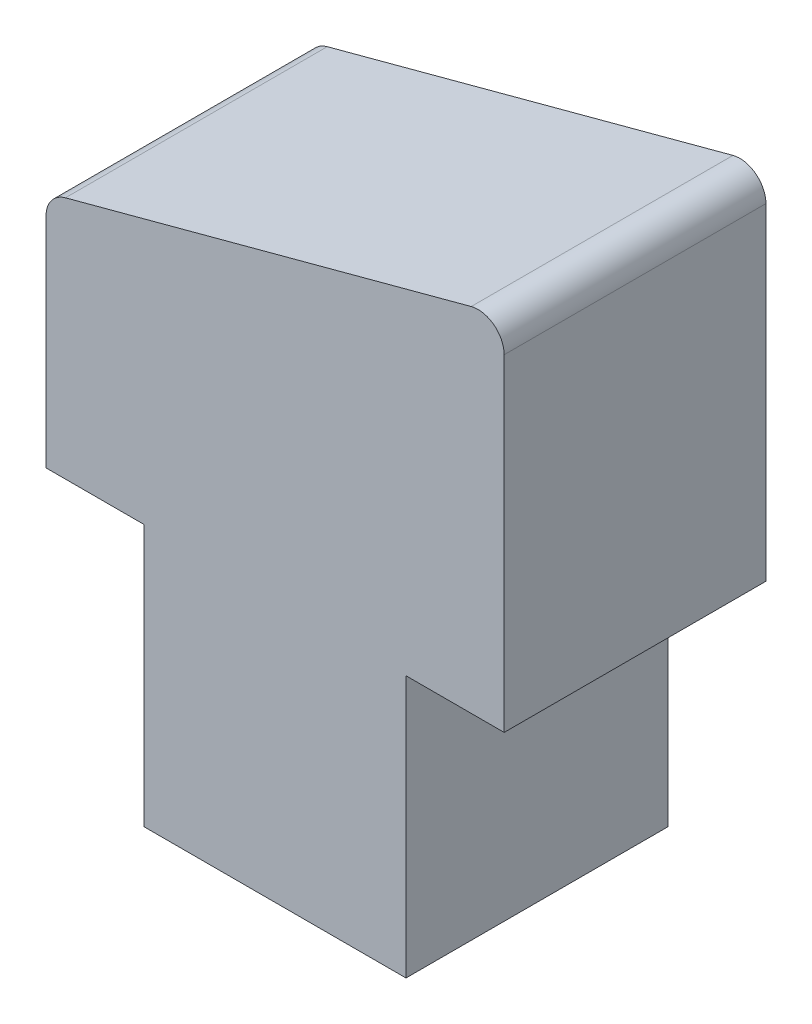
SolidWorks part; units mm, degrees
ref_plane "정면" through (0, 0, 0) normal (0, 0, 1) x (1, 0, 0)
ref_plane "윗면" through (0, 0, 0) normal (0, 1, 0) x (1, 0, 0)
ref_plane "우측면" through (0, 0, 0) normal (1, 0, 0) x (0, 0, -1)
sketch "Sketch2" plane through (0, 0, 0) normal (0, 1, 0) x (1, 0, 0)
  line L1 (-75, 30) -> (75, 30)
  line L2 (-75, 30) -> (-75, -30)
  line L3 (-75, -30) -> (75, -30)
  line L4 (75, 30) -> (75, -30)
  point P4 (0, 30)
  point P6 (-75, 0)
  dimension "D1" = 150
  dimension "D2" = 60
extrude "Extrude1" add sketch "Sketch2" along normal blind 20
sketch "Sketch3" plane through (0, 20, 0) normal (0, 1, 0) x (1, 0, 0)
  line L1 (-10.2, 23.1) -> (10.2, 23.1)
  line L2 (-10.2, 23.1) -> (-10.2, 2.7)
  line L3 (-10.2, 2.7) -> (10.2, 2.7)
  line L4 (10.2, 23.1) -> (10.2, 2.7)
  line L5 (-10.2, -2.7) -> (10.2, -2.7)
  line L6 (-10.2, -2.7) -> (-10.2, -23.1)
  line L7 (-10.2, -23.1) -> (10.2, -23.1)
  line L8 (10.2, -2.7) -> (10.2, -23.1)
  point P8 (0, -2.7)
  point P10 (0, 2.7)
  dimension "D1" = 20.4
  dimension "D2" = 20.4
  dimension "D3" = 20.4
  dimension "D4" = 20.4
  dimension "D5" = 5.4
  dimension "D6" = 2.7
extrude "Extrude2" cut sketch "Sketch3" against normal blind 20
sketch "Sketch4" plane through (0, 0, 0) normal (0, 0, 1) x (1, 0, 0)
  line L0 (0, 0) -> (0, 35) construction
  line L1 (0, 27.5) -> (-75, 47.5962) construction
  line L2 (-75, 20) -> (75, 20) construction
  line L3 (-75, 20) -> (-75, 0) construction
  line L4 (-75, 20) -> (-75, 47.5962)
  line L5 (-75, 47.5962) -> (-40, 38.218)
  line L6 (-40, 38.218) -> (-40, 20)
  line L7 (-75, 20) -> (-40, 20)
  dimension "D1" = 35
  dimension "D2" = 7.5
  dimension "D3" = 15
  dimension "D4" = 35
extrude "Extrude3" add sketch "Sketch4" along normal mid plane 20
mirror "Mirror1" about plane through (0, 0, 0) normal (1, 0, 0) of "Extrude3"
sketch "Sketch5" plane through (0, 0, -10) normal (0, 0, -1) x (-1, 0, 0)
  line L1 (-75, 20) -> (75, 20)
  line L2 (-75, 20) -> (-75, 0)
  line L3 (-75, 0) -> (75, 0)
  line L4 (75, 20) -> (75, 0)
  line L5 (0, 20) -> (75, 20)
  line L6 (0, 20) -> (0, 47.5962)
  line L7 (0, 47.5962) -> (75, 47.5962)
  line L8 (75, 20) -> (75, 47.5962)
  line M3 (-75, 20) -> (-40, 20)
extrude "Extrude4" cut sketch "Sketch5" against normal through all both and the other way through all contours L4 L1 L2 L3 M3 | L1 L8 L7 L6
sketch "Sketch6" plane through (0, 20, 0) normal (0, -1, 0) x (1, 0, 0)
  line L0 (75, -10) -> (40, -10) construction
  line L1 (67.5, -10) -> (47.5, -10)
  line L2 (67.5, -10) -> (67.5, 10)
  line L3 (67.5, 10) -> (47.5, 10)
  line L4 (47.5, -10) -> (47.5, 10)
  line L5 (75, 10) -> (40, 10) construction
  point P8 (57.5, 10)
  point P9 (57.5, 10)
  dimension "D1" = 20
extrude "Extrude5" add sketch "Sketch6" along normal blind 20
fillet "Fillet1" radius 2 2 edges at (40, 38.218, 0) (75, 47.5962, 0)
